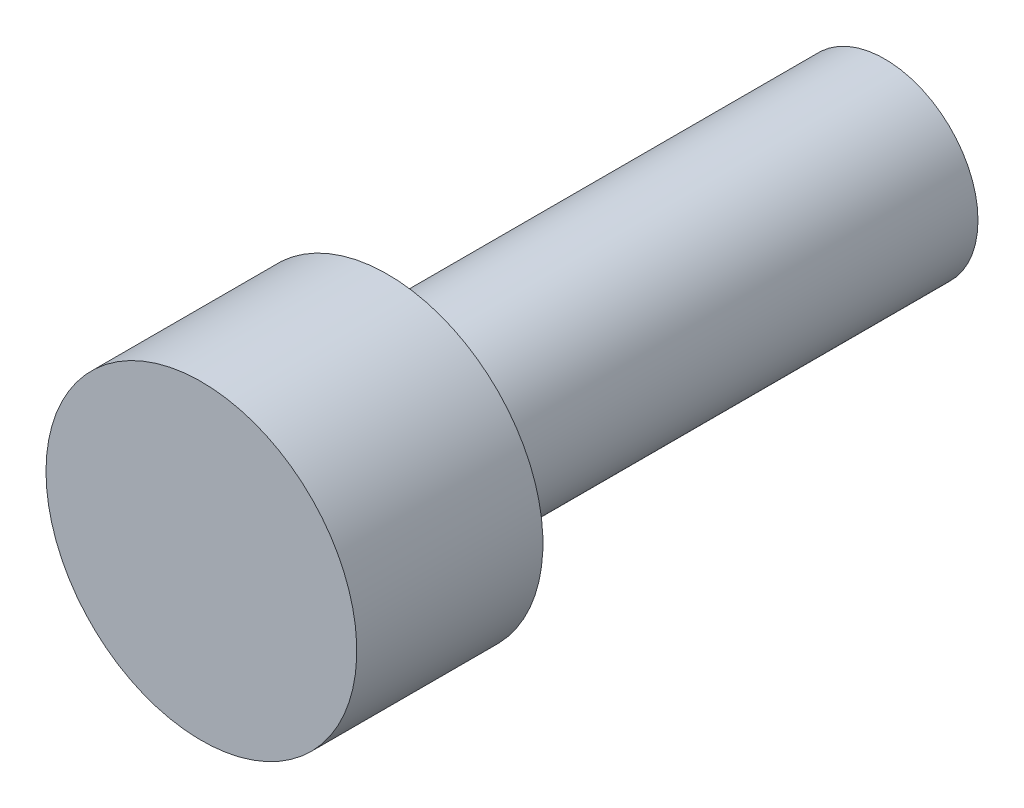
SolidWorks part; units mm, degrees
ref_plane "前视基准面" through (0, 0, 0) normal (0, 0, 1) x (1, 0, 0)
ref_plane "上视基准面" through (0, 0, 0) normal (0, 1, 0) x (1, 0, 0)
ref_plane "右视基准面" through (0, 0, 0) normal (1, 0, 0) x (0, 0, -1)
other "Configuration Table"
sketch "草图1" plane through (0, 0, 0) normal (0, 0, 1) x (1, 0, 0)
  circle A0 centre (0, 0) radius 3
extrude "凸台-拉伸1" add sketch "草图1" against normal blind 16
sketch "草图2" plane through (0, 0, 0) normal (0, 0, 1) x (1, 0, 0)
  circle A0 centre (0, 0) radius 5
extrude "凸台-拉伸2" add sketch "草图2" along normal blind 5.99
